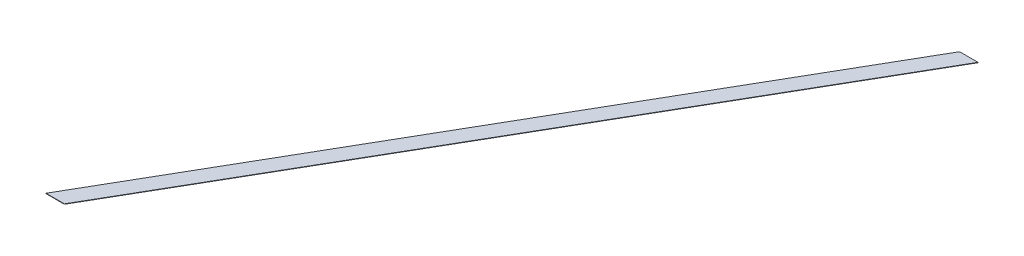
SolidWorks part; units mm, degrees
ref_plane "Front Plane" through (0, 0, 0) normal (0, 0, 1) x (1, 0, 0)
ref_plane "Top Plane" through (0, 0, 0) normal (0, 1, 0) x (1, 0, 0)
ref_plane "Right Plane" through (0, 0, 0) normal (1, 0, 0) x (0, 0, -1)
sketch "Sketch1" plane through (0, 0, 0) normal (0, 1, 0) x (1, 0, 0)
  line L0 (0, 0) -> (0, 101.6615)
  line L1 (0, 101.6615) -> (1523.0785, 2741.8387)
  line L2 (1523.0785, 2741.8387) -> (1581.7255, 2741.8387)
  line L3 (1581.7255, 2741.8387) -> (0, 0)
  line L4 (456.7373, 893.3918) -> (515.3843, 893.3918)
  dimension "D1" = 50.8
  dimension "D2" = 209.98
  dimension "D3" = 3048
  dimension "D4" = 1848.4469
extrude "Boss-Extrude1" add sketch "Sketch1" along normal blind 1.27 contours L1 L4 L3 L2
